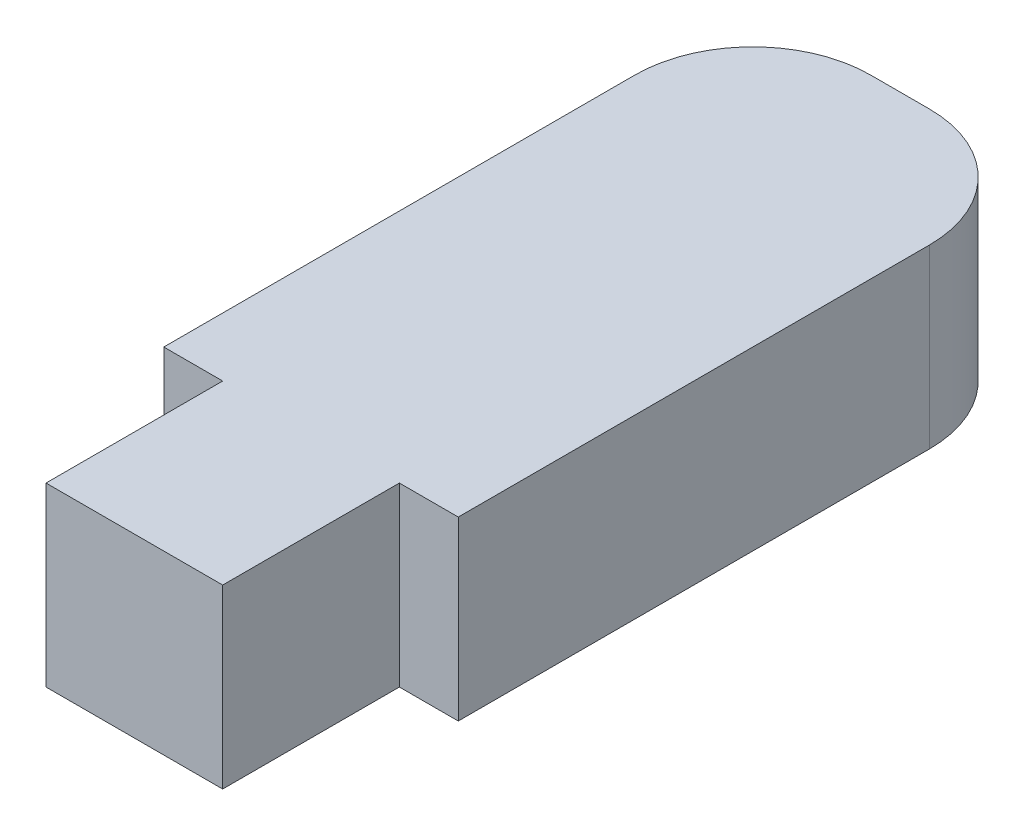
SolidWorks part; units mm, degrees
ref_plane "Front Plane" through (0, 0, 0) normal (0, 0, 1) x (1, 0, 0)
ref_plane "Top Plane" through (0, 0, 0) normal (0, 1, 0) x (1, 0, 0)
ref_plane "Right Plane" through (0, 0, 0) normal (1, 0, 0) x (0, 0, -1)
sketch "Sketch1" plane through (0, 0, 0) normal (0, 1, 0) x (1, 0, 0)
  line L0 (-1, -3) -> (-4, -3)
  line L1 (0, 0) -> (-1, 0)
  line L2 (0, 0) -> (0, 8)
  line L3 (-2, 10) -> (-3, 10)
  line L4 (-5, 0) -> (-5, 8)
  line L5 (-4, -3) -> (-4, 0)
  line L6 (-1, -3) -> (-1, 0)
  line L7 (-4, 0) -> (-5, 0)
  arc A0 (0, 8) -> (-2, 10) centre (-2, 8) ccw
  arc A1 (-5, 8) -> (-3, 10) centre (-3, 8) cw
  point P11 (0, 10)
  dimension "D5" = 2
  dimension "D1" = 5
  dimension "D2" = 3
  dimension "D3" = 10
  dimension "D4" = 3
extrude "Boss-Extrude1" add sketch "Sketch1" along normal blind 3
